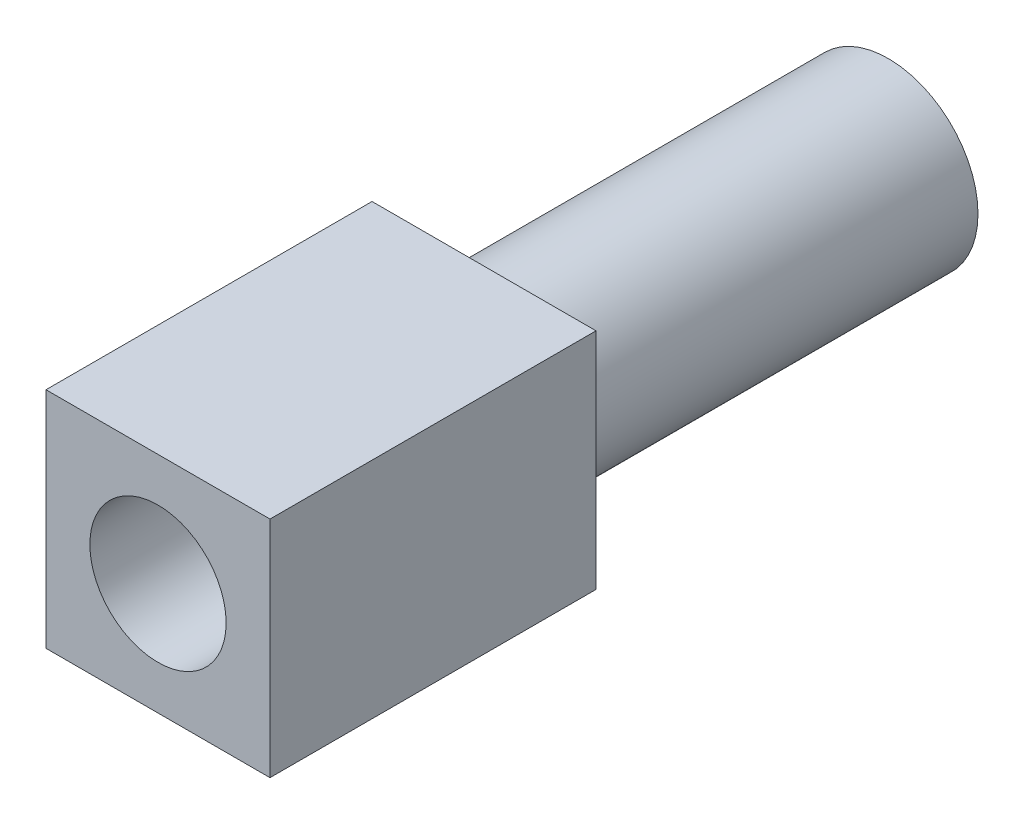
SolidWorks part; units mm, degrees
ref_plane "Plan de face" through (0, 0, 0) normal (0, 0, 1) x (1, 0, 0)
ref_plane "Plan de dessus" through (0, 0, 0) normal (0, 1, 0) x (1, 0, 0)
ref_plane "Plan de droite" through (0, 0, 0) normal (1, 0, 0) x (0, 0, -1)
sketch "Esquisse1" plane through (0, 0, 0) normal (0, 0, 1) x (1, 0, 0)
  line L1 (-37.0561, 15.4804) -> (-23.3161, 15.4804)
  line L2 (-37.0561, 15.4804) -> (-37.0561, 1.7404)
  line L3 (-37.0561, 1.7404) -> (-23.3161, 1.7404)
  line L4 (-23.3161, 15.4804) -> (-23.3161, 1.7404)
  dimension "D1" = 13.74
  dimension "D2" = 13.74
extrude "Boss.-Extru.1" add sketch "Esquisse1" along normal blind 20
sketch "Esquisse2" plane through (0, 0, 0) normal (0, 0, -1) x (-1, 0, 0)
  circle A1 centre (30.1861, 8.6104) radius 2.49
sketch "Esquisse3" plane through (0, 0, 20) normal (0, 0, 1) x (1, 0, 0)
  circle A0 centre (-30.1861, 8.6104) radius 4.18
extrude "Enlèv. mat.-Extru.2" cut sketch "Esquisse3" against normal blind 10
extrude "Boss.-Extru.4" add sketch "Esquisse2" along normal blind 24.8
sketch "Esquisse5" plane through (0, 0, -24.8) normal (0, 0, -1) x (-1, 0, 0)
  line L0 (27.6961, 8.6104) -> (29.6258, 11.0365)
  circle A0 centre (30.1861, 8.6104) radius 2.49 construction
  arc A1 (27.6961, 8.6104) -> (29.6258, 11.0365) centre (30.1861, 8.6104) ccw
  spline S0 degree 1 poles (29.6258, 11.0365) (27.6961, 8.6104) knots 0 0 1 1
  circle M2 centre (30.1861, 8.6104) radius 2.49
  dimension "D1" = 3.1
extrude "Enlèv. mat.-Extru.4" cut sketch "Esquisse5" against normal blind 24.8 contours L0 M2
sketch "Esquisse6" plane through (0, 0, 0) normal (0, 0, -1) x (-1, 0, 0)
  circle A0 centre (30.1861, 8.6104) radius 5.5
  circle A2 centre (30.1861, 8.6104) radius 2.49
extrude "Boss.-Extru.5" add sketch "Esquisse6" along normal blind 24.8
